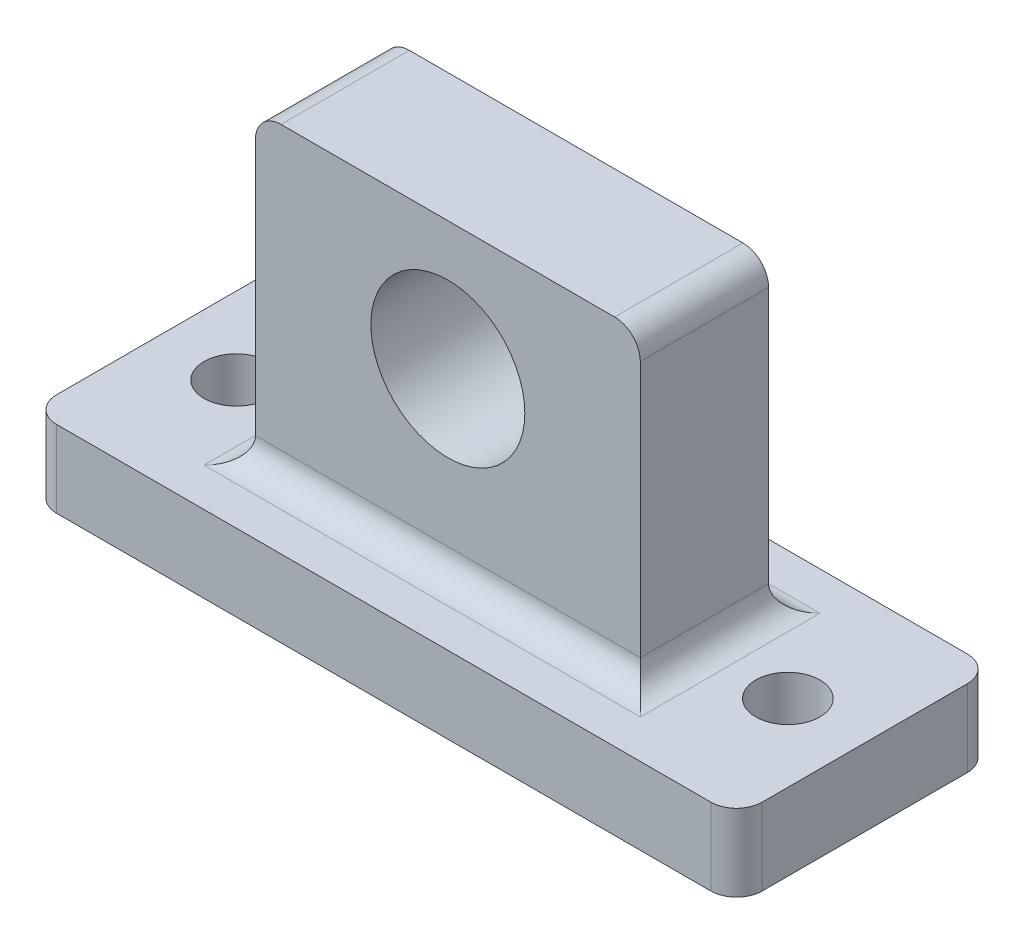
SolidWorks part; units mm, degrees
material "Plain Carbon Steel"
ref_plane "Front" through (0, 0, 0) normal (0, 0, 1) x (1, 0, 0)
ref_plane "Top" through (0, 0, 0) normal (0, 1, 0) x (1, 0, 0)
ref_plane "Right" through (0, 0, 0) normal (1, 0, 0) x (0, 0, -1)
sketch "Sketch1" plane through (0, 0, 0) normal (0, 0, 1) x (1, 0, 0)
  line L1 (0, 0) -> (30, 0)
  line L2 (0, 0) -> (0, 30)
  line L3 (0, 30) -> (30, 30)
  line L4 (30, 0) -> (30, 30)
  circle A0 centre (15, 20) radius 6
  dimension "D3" = 12
  dimension "D1" = 30
  dimension "D2" = 30
  dimension "D4" = 20
extrude "Boss-Extrude1" add sketch "Sketch1" along normal blind 10
sketch "Sketch2" plane through (0, 0, 0) normal (0, -1, 0) x (-1, 0, 0)
  line L0 (0, -10) -> (0, 0) construction
  line L1 (12.5, -15) -> (-42.5, -15)
  line L2 (12.5, -15) -> (12.5, 5)
  line L3 (12.5, 5) -> (-42.5, 5)
  line L4 (-42.5, -15) -> (-42.5, 5)
  line L5 (12.5, -15) -> (-42.5, 5) construction
  line L6 (12.5, 5) -> (-42.5, -15) construction
  line L7 (0, 0) -> (-30, 0) construction
  line L8 (-15, 5) -> (-15, -15) construction
  circle A0 centre (6.5, -5) radius 2.5
  circle A1 centre (-36.5, -5) radius 2.5
  point P0 (-15, -5)
  dimension "D5" = 5
  dimension "D1" = 55
  dimension "D2" = 12.5
  dimension "D3" = 20
  dimension "D4" = 5
  dimension "D6" = 6
extrude "Boss-Extrude2" add sketch "Sketch2" against normal blind 6
fillet "Fillet1" radius 2 10 edges at (15, 6, 10) (15, 6, 0) (30, 6, 5) (0, 6, 5) (-12.5, 3, 15) (-12.5, 3, -5) (42.5, 3, 15) (42.5, 3, -5) (0, 30, 5) (30, 30, 5)
